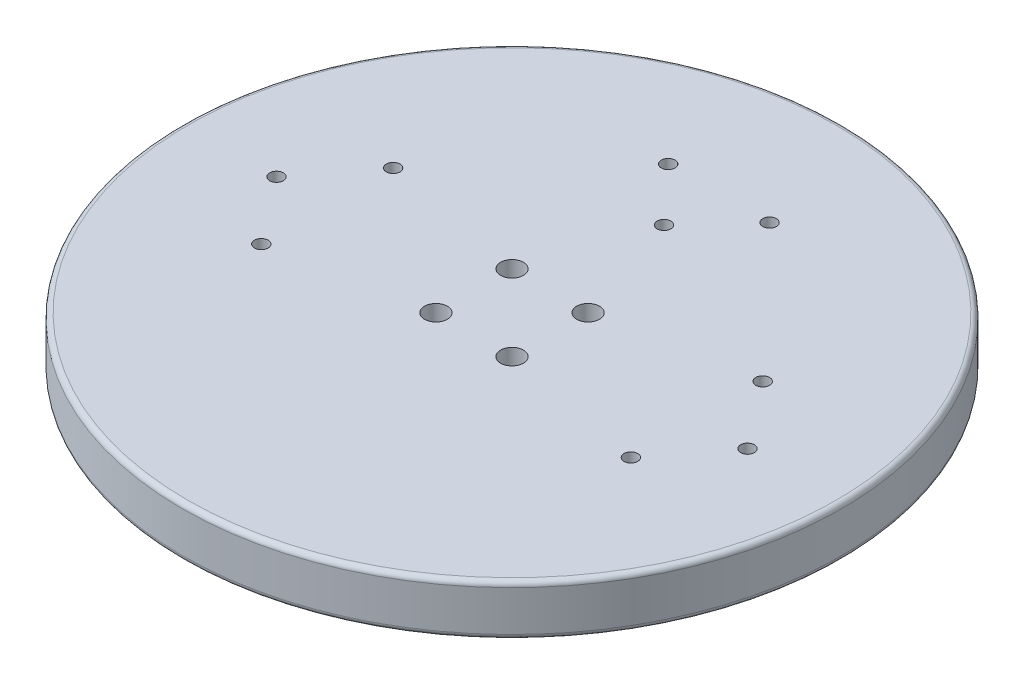
SolidWorks part; units mm, degrees
material "Delrin 2700 NC010, Low Viscosity Acetal Copolymer (SS)"
ref_plane "Front Plane" through (0, 0, 0) normal (0, 0, 1) x (1, 0, 0)
ref_plane "Top Plane" through (0, 0, 0) normal (0, 1, 0) x (1, 0, 0)
ref_plane "Right Plane" through (0, 0, 0) normal (1, 0, 0) x (0, 0, -1)
sketch "Sketch1" plane through (0, 0, 0) normal (0, 1, 0) x (1, 0, 0)
  circle A0 centre (0, 0) radius 65
  dimension "D1" = 130
extrude "Boss-Extrude1" add sketch "Sketch1" along normal blind 10
fillet "Fillet1" radius 1 2 edges at (0, 0, 65) (0, 10, 65)
hole_wizard "#6-32 Tapped Hole1" positions "Sketch2" profile "Sketch3" tap size "#6-32" standard "ANSI Inch" end condition through all
sketch "Sketch2" plane through (0, 0, 0) normal (0, 1, 0) x (1, 0, 0)
  point P0 (-46.445, 0)
  point P2 (46.445, 0)
  point P4 (-36.445, 13)
  point P6 (-36.445, -13)
  point P8 (36.445, -13)
  point P10 (36.445, 13)
  point P15 (10.0012, 40.8)
  point P18 (0.0012, 29.9781)
  point P21 (-9.9988, 40.8)
  dimension "D1" = 46.445
  dimension "D2" = 46.445
  dimension "D3" = 36.445
  dimension "D4" = 36.445
  dimension "D5" = 13
  dimension "D6" = 13
sketch "Sketch3" plane through (-46.445, 0, 0) normal (1, 0, 0) x (0, 0, -1)
  line L0 (0, 0) -> (0, 10)
  line L1 (0, 10) -> (1.3525, 10)
  line L2 (1.3525, 10) -> (1.3525, 0)
  line L5 (1.3525, 0) -> (0, 0)
  line L11 (0, -6.35) -> (0, 107.95) construction
  dimension "Thru Tap Drill Dia." = 2.7051
  dimension "Thru Tap Drill Depth" = 10
cosmetic thread "Hole Thread1" parameters "D2"=3.5052
cosmetic thread "Hole Thread2" parameters "D2"=3.5052
cosmetic thread "Hole Thread3" parameters "D2"=3.5052
cosmetic thread "Hole Thread4" parameters "D2"=3.5052
cosmetic thread "Hole Thread5" parameters "D2"=3.5052
cosmetic thread "Hole Thread6" parameters "D2"=3.5052
cosmetic thread "Hole Thread9" parameters "D2"=3.5052
cosmetic thread "Hole Thread10" parameters "D2"=3.5052
cosmetic thread "Hole Thread11" parameters "D2"=3.5052
hole_wizard "#4-40 Tapped Hole1" [suppressed] positions "Sketch5" profile "Sketch6" tap size "#4-40" standard "ANSI Inch"
sketch "Sketch5" plane through (0, 0, 0) normal (0, -1, 0) x (-1, 0, 0)
  circle A0 centre (-36.145, 0) radius 1.3526 construction
  point P0 (-48.145, 27.124)
  point P2 (-48.145, -27.124)
  dimension "D1" = 12
  dimension "D2" = 27.124
  dimension "D3" = 27.124
sketch "Sketch6" plane through (48.145, 0, -27.124) normal (1, 0, 0) x (0, 0, -1)
  line L0 (0, 0) -> (0, 25.4)
  line L1 (0, 25.4) -> (1.1303, 25.4)
  line L2 (1.1303, 25.4) -> (1.1303, 0)
  line L5 (1.1303, 0) -> (0, 0)
  line L11 (0, -6.35) -> (0, 107.95) construction
  dimension "Thru Tap Drill Dia." = 2.2606
  dimension "Thru Tap Drill Depth" = 25.4
cosmetic thread "Hole Thread7" [suppressed] parameters "D2"=2.8448
cosmetic thread "Hole Thread8" [suppressed] parameters "D2"=2.8448
hole_wizard "#8 Clearance Hole1" positions "Sketch7" profile "Sketch8" hole size "#8" standard "ANSI Inch" end condition through all
sketch "Sketch7" plane through (0, 0, 0) normal (0, -1, 0) x (-1, 0, 0)
  circle A0 centre (0, 0) radius 16.5 construction
  point P0 (7.5, -7.5)
  point P2 (-7.5, -7.5)
  point P4 (7.5, 7.5)
  point P6 (-7.5, 7.5)
  dimension "D5" = 33
  dimension "D1" = 7.5
  dimension "D2" = 7.5
  dimension "D3" = 7.5
  dimension "D4" = 7.5
sketch "Sketch8" plane through (-7.5, 0, 7.5) normal (1, 0, 0) x (0, 0, -1)
  line L0 (0, 0) -> (0, 10)
  line L1 (0, 10) -> (2.2479, 10)
  line L2 (2.2479, 10) -> (2.2479, 0)
  line L5 (2.2479, 0) -> (0, 0)
  line L11 (0, -6.35) -> (0, 107.95) construction
  dimension "Thru Hole Dia." = 4.4958
  dimension "Thru Hole Depth" = 10
equation "\"D2@Sketch2\"=\"D1@Sketch2\""
equation "\"D4@Sketch2\"=\"D3@Sketch2\""
equation "\"D6@Sketch2\"=\"D5@Sketch2\""
equation "\"D2@Sketch5\"=\"D3@Sketch5\""
equation "\"D2@Sketch7\"=\"D1@Sketch7\""
equation "\"D3@Sketch7\"=\"D4@Sketch7\""
equation "\"D1@Sketch2\"=92.89/2"
equation "\"D3@Sketch2\"=72.89/2"
